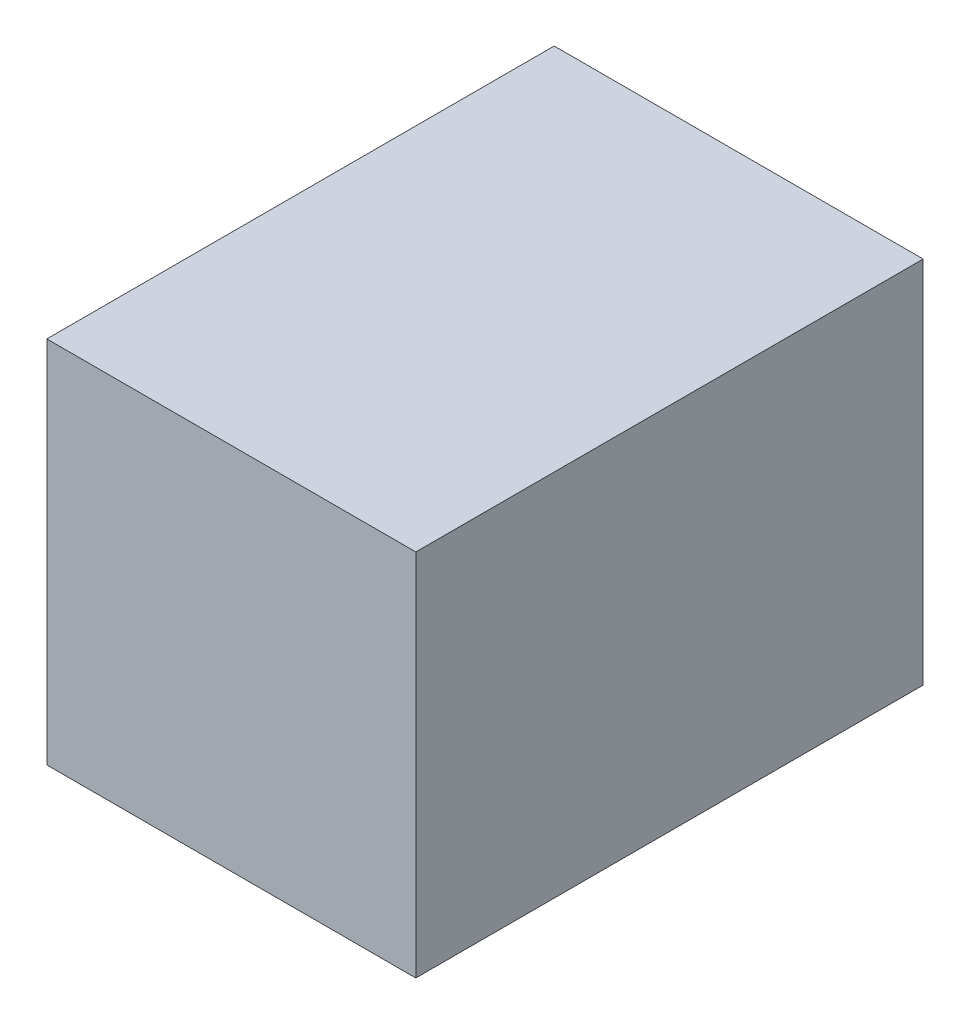
SolidWorks part; units mm, degrees
ref_plane "Front Plane" through (0, 0, 0) normal (0, 0, 1) x (1, 0, 0)
ref_plane "Top Plane" through (0, 0, 0) normal (0, 1, 0) x (1, 0, 0)
ref_plane "Right Plane" through (0, 0, 0) normal (1, 0, 0) x (0, 0, -1)
sketch "Sketch1" plane through (0, 0, 0) normal (0, 0, 1) x (1, 0, 0)
  line L1 (0, 0) -> (25.4, 0)
  line L2 (0, 0) -> (0, 25.4)
  line L3 (0, 25.4) -> (25.4, 25.4)
  line L4 (25.4, 0) -> (25.4, 25.4)
  dimension "D1" = 25.4
  dimension "D2" = 25.4
extrude "Boss-Extrude1" add sketch "Sketch1" along normal blind 34.925
